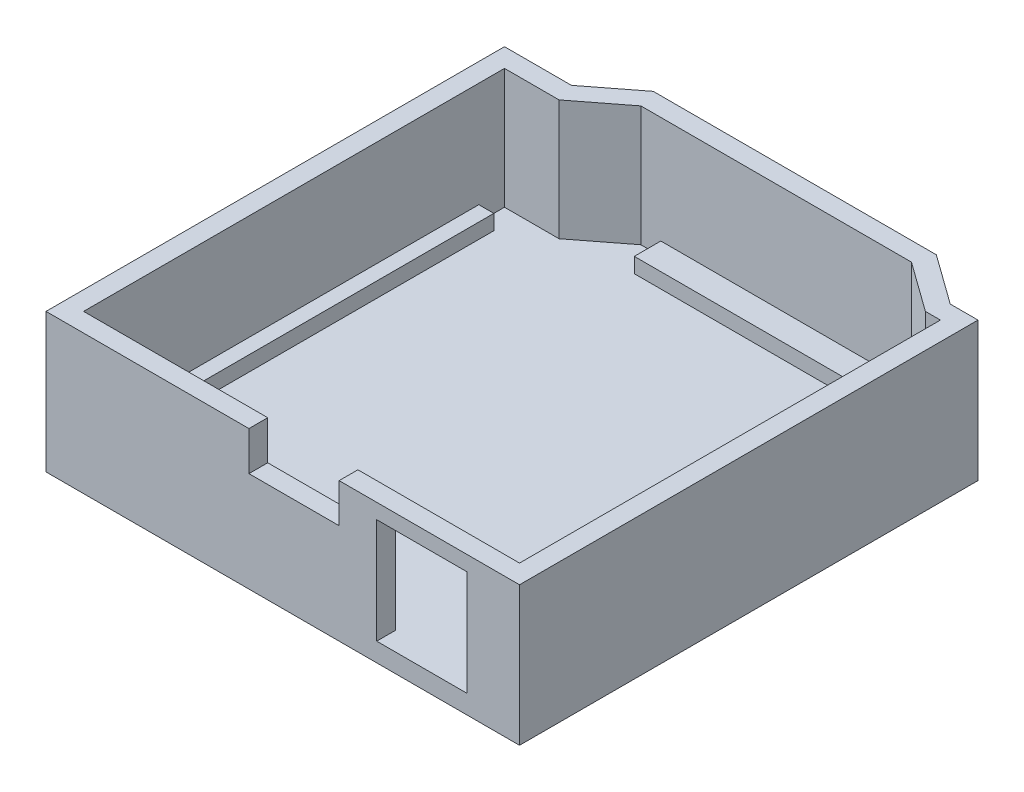
SolidWorks part; units mm, degrees
ref_plane "Front Plane" through (0, 0, 0) normal (0, 0, 1) x (1, 0, 0)
ref_plane "Top Plane" through (0, 0, 0) normal (0, 1, 0) x (1, 0, 0)
ref_plane "Right Plane" through (0, 0, 0) normal (1, 0, 0) x (0, 0, -1)
sketch "Sketch1" plane through (0, 0, 0) normal (0, 1, 0) x (1, 0, 0)
  line L0 (0, 0) -> (0, 56)
  line L1 (0, 56) -> (7.2606, 56)
  line L2 (7.2606, 56) -> (13.3994, 60.7502)
  line L3 (13.3994, 60.7502) -> (49.3994, 60.7502)
  line L4 (0, 0) -> (58, 0)
  line L5 (58, 0) -> (58, 56)
  line L7 (58, 56) -> (56, 56)
  line L8 (56, 56) -> (49.3994, 60.7502)
  dimension "D1" = 56
  dimension "D2" = 58
  dimension "D3" = 2
  dimension "D4" = 36
extrude "Boss-Extrude1" add sketch "Sketch1" along normal blind 16
shell "Shell1" thickness 2.5
sketch "Sketch2" plane through (0, 0, 0) normal (0, 0, -1) x (-1, 0, 0)
  line L5 (2.5, -2.5) -> (-60.5, -2.5) construction
  line L10 (-60.5, 16) -> (-60.5, -2.5) construction
  line L11 (-41.5, 14) -> (-53.5, 14)
  line L12 (-41.5, 14) -> (-41.5, 0)
  line L13 (-41.5, 0) -> (-53.5, 0)
  line L14 (-53.5, 14) -> (-53.5, 0)
  line L15 (2.5, 16) -> (-60.5, 16) construction
  line L16 (-24.5, 10.8048) -> (-36.5, 10.8048)
  line L17 (-24.5, 10.8048) -> (-24.5, 16)
  line L18 (-24.5, 16) -> (-36.5, 16)
  line L19 (-36.5, 10.8048) -> (-36.5, 16)
  dimension "D1" = 2.5
  dimension "D2" = 36
  dimension "D3" = 12
  dimension "D4" = 7
  dimension "D5" = 12
extrude "Cut-Extrude1" cut sketch "Sketch2" against normal blind 4
sketch "Sketch3" plane through (0, 0, 0) normal (0, 1, 0) x (1, 0, 0)
  line L0 (0, 56) -> (0, 0) construction
  line L1 (0, 52.5835) -> (2, 52.5835)
  line L2 (0, 52.5835) -> (0, 2.5835)
  line L3 (0, 2.5835) -> (2, 2.5835)
  line L4 (2, 52.5835) -> (2, 2.5835)
  line L7 (57.8762, 52.5835) -> (56.0617, 52.5835)
  line L8 (57.8762, 2.5835) -> (56.0617, 2.5835)
  line L9 (56.0617, 52.5835) -> (56.0617, 2.5835)
  line L10 (57.8762, 52.5835) -> (57.8762, 2.5835)
  dimension "D1" = 2
  dimension "D2" = 50
extrude "Boss-Extrude2" add sketch "Sketch3" along normal blind 2
sketch "Sketch4" plane through (0, 0, 0) normal (0, 1, 0) x (1, 0, 0)
  line L1 (16.2938, 60.5067) -> (47.3114, 60.5067)
  line L2 (16.2938, 60.5067) -> (16.2938, 56.9763)
  line L3 (16.2938, 56.9763) -> (47.3114, 56.9763)
  line L4 (47.3114, 60.5067) -> (47.3114, 56.9763)
extrude "Boss-Extrude3" add sketch "Sketch4" along normal blind 2
